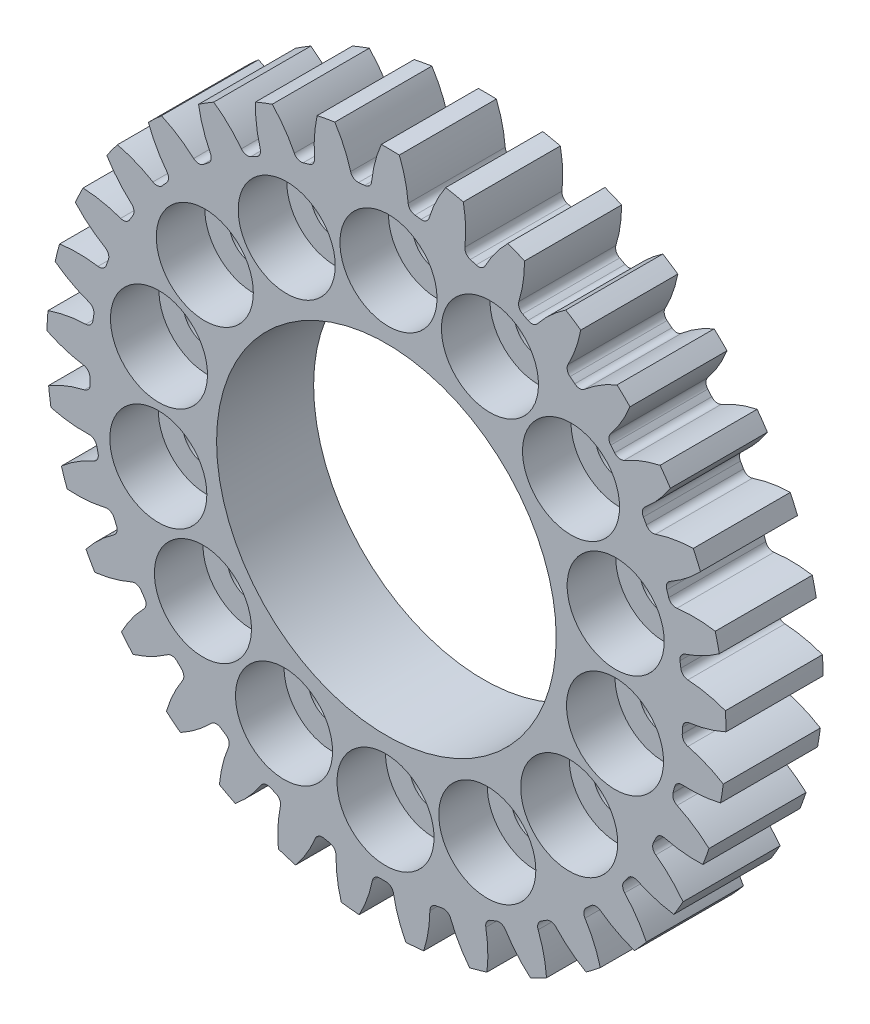
SolidWorks part; units mm, degrees
ref_plane "Front" through (0, 0, 0) normal (0, 0, 1) x (1, 0, 0)
ref_plane "Top" through (0, 0, 0) normal (0, 1, 0) x (1, 0, 0)
ref_plane "Right" through (0, 0, 0) normal (1, 0, 0) x (0, 0, -1)
sketch "Sketch3" plane through (0, 0, 0) normal (0, 0, 1) x (1, 0, 0)
  circle A0 centre (0, 0) radius 44.45
  dimension "od" = 88.9
extrude "gearBody" add sketch "Sketch3" along normal blind 12.7
sketch "Sketch2" plane through (0, 0, 0) normal (0, 0, 1) x (1, 0, 0)
  line L0 (0, 0) -> (37.4865, 15.5274) construction
  line L1 (50.1399, -12.16) -> (0, 0) construction
  line L2 (0, 0) -> (36.3143, 0) construction
  line L3 (41.907, -0.5038) -> (41.6735, -4.4459) construction
  line L5 (41.7902, -2.4749) -> (0, 0) construction
  line L7 (0, 0) -> (40.5751, 0) construction
  arc A0 (40.5669, -0.8143) -> (40.3795, -3.9794) centre (0, 0) ccw construction
  arc A1 (44.448, 0.4251) -> (44.0871, -5.6683) centre (0, 0) ccw construction
  arc A2 (41.907, -0.5038) -> (41.6735, -4.4459) centre (0, 0) ccw construction
  arc A3 (38.7175, -2.695) -> (38.765, -1.8936) centre (0, 0) ccw
  arc A4 (50.1399, -12.16) -> (39.4596, -3.719) centre (35.3918, -19.8433) ccw
  arc A5 (50.1399, -12.16) -> (51.2247, 6.1571) centre (0, 0) ccw
  arc A6 (51.2247, 6.1571) -> (39.6227, -0.9643) centre (37.4865, 15.5274) cw
  arc A7 (38.765, -1.8936) -> (39.6227, -0.9643) centre (39.7493, -1.9417) cw
  arc A8 (39.4596, -3.719) -> (38.7175, -2.695) centre (39.7007, -2.7634) cw
  point P6 (51.2247, 6.1571)
  point P22 (50.1399, -12.16)
  dimension "baseDia" = 81.1501
  dimension "od" = 88.9
  dimension "pd" = 83.82
  dimension "rd" = 77.6224
  dimension "rFillet" = 0.9855
  dimension "pointX" = 51.2247
  dimension "pointY" = 6.1571
  dimension "CTT" = 3.9421
  dimension "flankCenterAngle" = 22.5
extrude "toothCut" cut sketch "Sketch2" along normal through all
pattern_circular "CirPattern1" count 33 over 360 about axis through (0, 0, 0) along (0, 0, 1) of "toothCut"
sketch "hub1Dia" plane through (0, 0, 0) normal (0, 0, -1) x (-1, 0, 0)
  circle A0 centre (0, 0) radius 12.7
  dimension "hub1Dia" = 25.4
sketch "hub2Dia" plane through (0, 0, 12.7) normal (0, 0, 1) x (1, 0, 0)
  circle A0 centre (0, 0) radius 12.7
  dimension "hub2dia" = 25.4
sketch "boreDia" plane through (0, 0, 0) normal (0, 0, 1) x (1, 0, 0)
  circle A0 centre (0, 0) radius 22.225
  dimension "boreDia" = 44.45
extrude "bore" cut sketch "boreDia" against normal mid plane 25400
sketch "Sketch4" plane through (0, 0, 0) normal (0, 0, -1) x (-1, 0, 0)
  circle A11 centre (-29.9196, -7.0281) radius 3.175
  circle A14 centre (-30.0058, 6.6134) radius 3.175
  circle A15 centre (-24.1646, 18.9413) radius 3.175
  circle A16 centre (-13.553, 27.514) radius 3.175
  circle A17 centre (-0.2728, 30.6335) radius 3.175
  circle A18 centre (13.0458, 27.682) radius 3.175
  circle A19 centre (23.7649, 19.2441) radius 3.175
  circle A20 centre (29.7614, 6.9909) radius 3.175
  circle A21 centre (29.8475, -6.6505) radius 3.175
  circle A22 centre (24.0064, -18.9785) radius 3.175
  circle A23 centre (13.3948, -27.5512) radius 3.175
  circle A24 centre (0.1145, -30.6707) radius 3.175
  circle A25 centre (-13.2041, -27.7192) radius 3.175
  circle A26 centre (-23.9232, -19.2813) radius 3.175
  point P30 (-0.0791, -0.0186)
  dimension "D1" = 14
  dimension "D2" = 30.6527
extrude "Cut-Extrude1" cut sketch "Sketch4" against normal through all both and the other way through all
sketch "Sketch7" plane through (0, 0, 12.7) normal (0, 0, 1) x (1, 0, 0)
  circle A2 centre (-29.7614, 6.9909) radius 6.35
  circle A3 centre (-29.7614, 6.9909) radius 6.35
  circle A5 centre (-23.7649, 19.2441) radius 6.35
  circle A6 centre (-23.7649, 19.2441) radius 6.35
  circle A8 centre (-13.0458, 27.682) radius 6.35
  circle A9 centre (-13.0458, 27.682) radius 6.35
  circle A11 centre (0.2728, 30.6335) radius 6.35
  circle A12 centre (0.2728, 30.6335) radius 6.35
  circle A14 centre (13.553, 27.514) radius 6.35
  circle A15 centre (13.553, 27.514) radius 6.35
  circle A17 centre (24.1646, 18.9413) radius 6.35
  circle A18 centre (24.1646, 18.9413) radius 6.35
  circle A20 centre (30.0058, 6.6134) radius 6.35
  circle A21 centre (30.0058, 6.6134) radius 6.35
  circle A23 centre (29.9196, -7.0281) radius 6.35
  circle A24 centre (29.9196, -7.0281) radius 6.35
  circle A26 centre (23.9232, -19.2813) radius 6.35
  circle A27 centre (23.9232, -19.2813) radius 6.35
  circle A29 centre (13.2041, -27.7192) radius 6.35
  circle A30 centre (13.2041, -27.7192) radius 6.35
  circle A32 centre (-0.1145, -30.6707) radius 6.35
  circle A33 centre (-0.1145, -30.6707) radius 6.35
  circle A35 centre (-13.3948, -27.5512) radius 6.35
  circle A36 centre (-13.3948, -27.5512) radius 6.35
  circle A38 centre (-24.0064, -18.9785) radius 6.35
  circle A39 centre (-24.0064, -18.9785) radius 6.35
  circle A41 centre (-29.8475, -6.6505) radius 6.35
  circle A42 centre (-29.8475, -6.6505) radius 6.35
  dimension "D1" = 3.175
  dimension "D2" = 3.175
  dimension "D3" = 3.175
  dimension "D4" = 3.175
  dimension "D5" = 3.175
  dimension "D6" = 3.175
  dimension "D7" = 3.175
  dimension "D8" = 3.175
  dimension "D9" = 3.175
  dimension "D10" = 3.175
  dimension "D11" = 3.175
  dimension "D12" = 3.175
  dimension "D13" = 3.175
  dimension "D14" = 3.175
extrude "Cut-Extrude2" cut sketch "Sketch7" against normal blind 6.35
